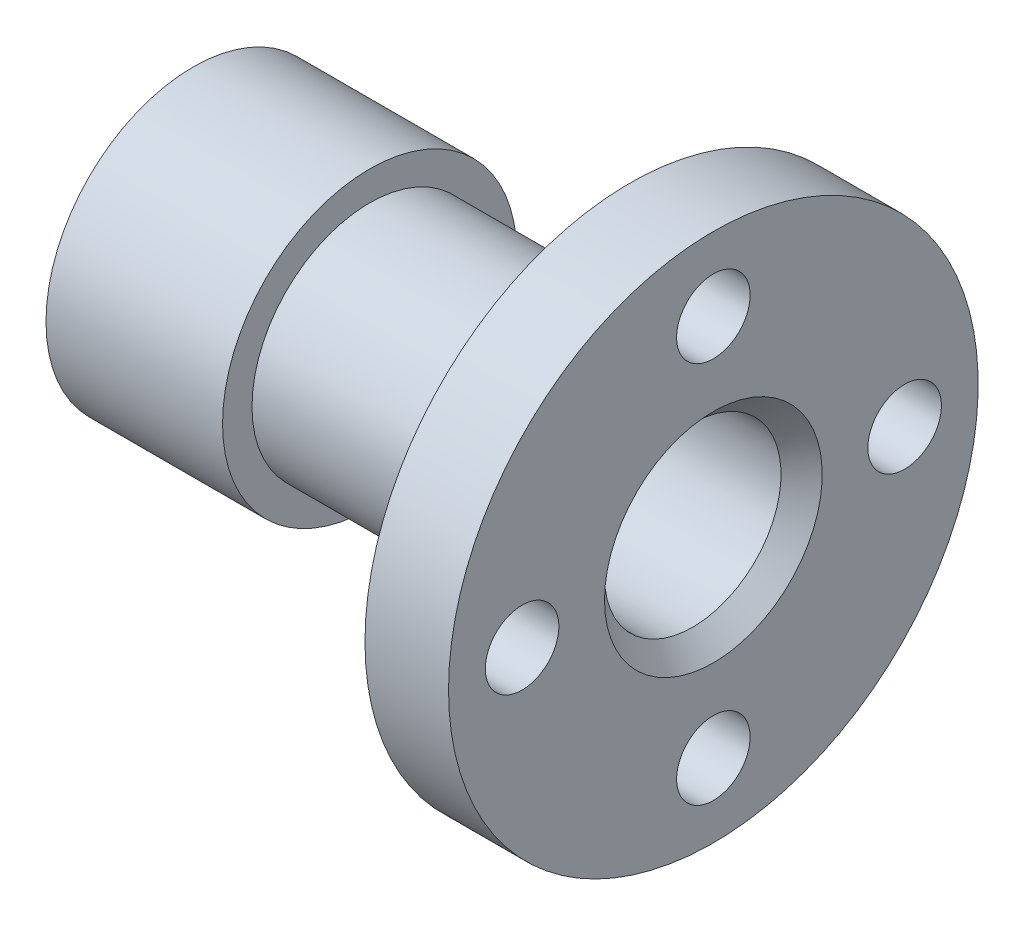
SolidWorks part; units mm, degrees
ref_plane "Alzado" through (0, 0, 0) normal (0, 0, 1) x (1, 0, 0)
ref_plane "Planta" through (0, 0, 0) normal (0, 1, 0) x (1, 0, 0)
ref_plane "Vista lateral" through (0, 0, 0) normal (1, 0, 0) x (0, 0, -1)
sketch "Croquis1" plane through (0, 0, 0) normal (0, 0, 1) x (1, 0, 0)
  line L0 (0, 0) -> (0, 15) construction
  line L1 (0, 0) -> (73.5897, 0) construction
  line L2 (19.7846, 15) -> (-44.6154, 15)
  line L3 (-44.6154, 15) -> (-44.6154, 19)
  line L4 (-44.6154, 19) -> (-68.6154, 19)
  line L5 (-68.6154, 19) -> (-68.6154, 25)
  line L6 (-68.6154, 25) -> (-38.6154, 25)
  line L7 (-38.6154, 25) -> (-38.6154, 20)
  line L8 (-38.6154, 20) -> (5.5846, 20)
  line L9 (19.7846, 15) -> (19.7846, 45)
  line L10 (19.7846, 45) -> (5.5846, 45)
  line L11 (5.5846, 45) -> (5.5846, 20)
  dimension "D1" = 15
  dimension "D2" = 64.4
  dimension "D3" = 4
  dimension "D4" = 24
  dimension "D5" = 6
  dimension "D6" = 30
  dimension "D7" = 5
  dimension "D8" = 44.2
  dimension "D9" = 30
revolve "Revolución1" add sketch "Croquis1" angle 360 about L1
chamfer "Chaflán1" distance 3.5 angle 45 1 edges at (19.7846, 0, 15)
sketch "Croquis2" plane through (5.5846, 0, 0) normal (-1, 0, 0) x (0, 0, 1)
  line L0 (0, 0) -> (0, 32.5) construction
  line L1 (0, 0) -> (32.5, 0) construction
  circle A0 centre (0, 32.5) radius 6.25
  circle A1 centre (0, -32.5) radius 6.25
  circle A2 centre (32.5, 0) radius 6.25
  circle A3 centre (-32.5, 0) radius 6.25
  point P10 (0, 0)
  dimension "D2" = 12.5
  dimension "D4" = 12.5
  dimension "D1" = 32.5
  dimension "D3" = 32.5
extrude "Cortar-Extruir2" cut sketch "Croquis2" against normal blind 27 contours A1 | A2 | A0 | A3
